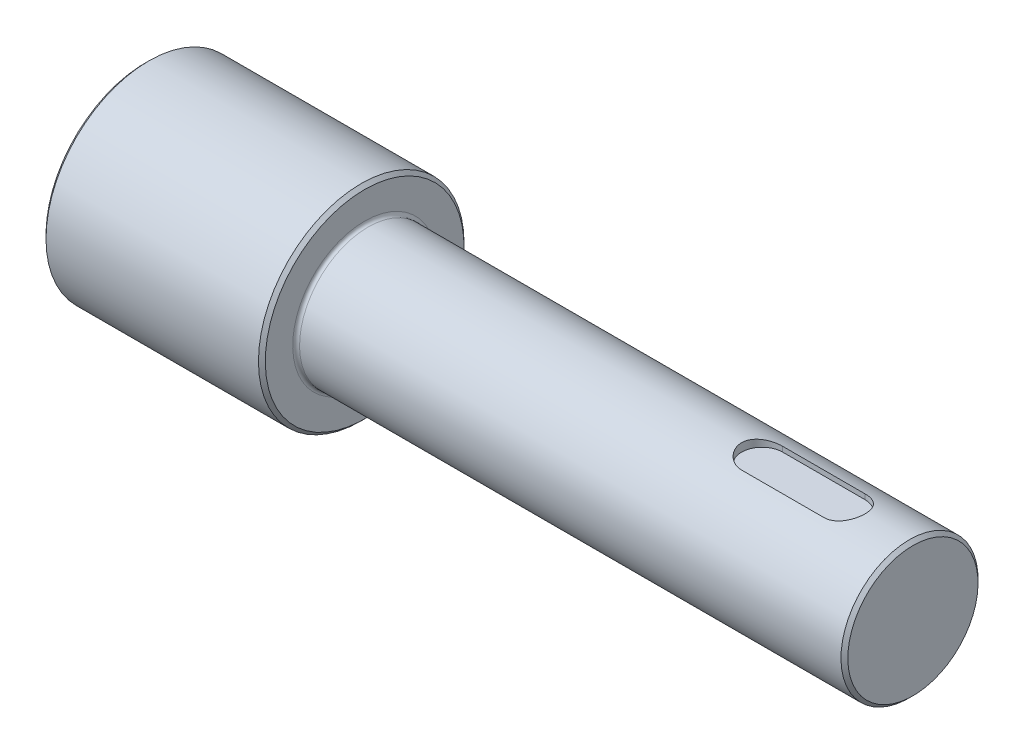
SolidWorks part; units mm, degrees
ref_plane "Спереди" through (0, 0, 0) normal (0, 0, 1) x (1, 0, 0)
ref_plane "Сверху" through (0, 0, 0) normal (0, 1, 0) x (1, 0, 0)
ref_plane "Справа" through (0, 0, 0) normal (1, 0, 0) x (0, 0, -1)
sketch "Эскиз1" plane through (0, 0, 0) normal (0, 0, 1) x (1, 0, 0)
  line L0 (0, 0) -> (0, 15)
  line L1 (0, 15) -> (32, 15)
  line L3 (32, 10) -> (112, 10)
  line L5 (112, 0) -> (0, 0)
  line L6 (112, 10) -> (112, 0)
  line L7 (32, 10) -> (32, 15)
  dimension "D1" = 15
  dimension "D2" = 32
  dimension "D3" = 80
  dimension "D4" = 10
revolve "Повернуть1" add sketch "Эскиз1" angle 360 about L5
chamfer "Фаска1" distance 0.5 angle 45 3 edges at (32, 15, 0) (112, 10, 0) (0, 15, 0)
fillet "Скругление1" radius 0.5 1 edges at (32, 10, 0)
ref_plane "Плоскость1" through (0, 10, 0) normal (0, 1, 0) x (1, 0, 0)
sketch "Эскиз2" plane through (0, 10, 0) normal (0, 1, 0) x (1, 0, 0)
  line L0 (90, 0) -> (102, 0) construction
  line L1 (90, 3) -> (102, 3)
  line L2 (90, -3) -> (102, -3)
  line L3 (112, -9.5) -> (112, 9.5) construction
  arc A0 (90, 3) -> (90, -3) centre (90, 0) ccw
  arc A1 (102, -3) -> (102, 3) centre (102, 0) ccw
  point P3 (96, 0)
  dimension "D1" = 6
  dimension "D2" = 12
  dimension "D3" = 10
extrude "Вырез-Вытянуть1" cut sketch "Эскиз2" against normal blind 1.2
